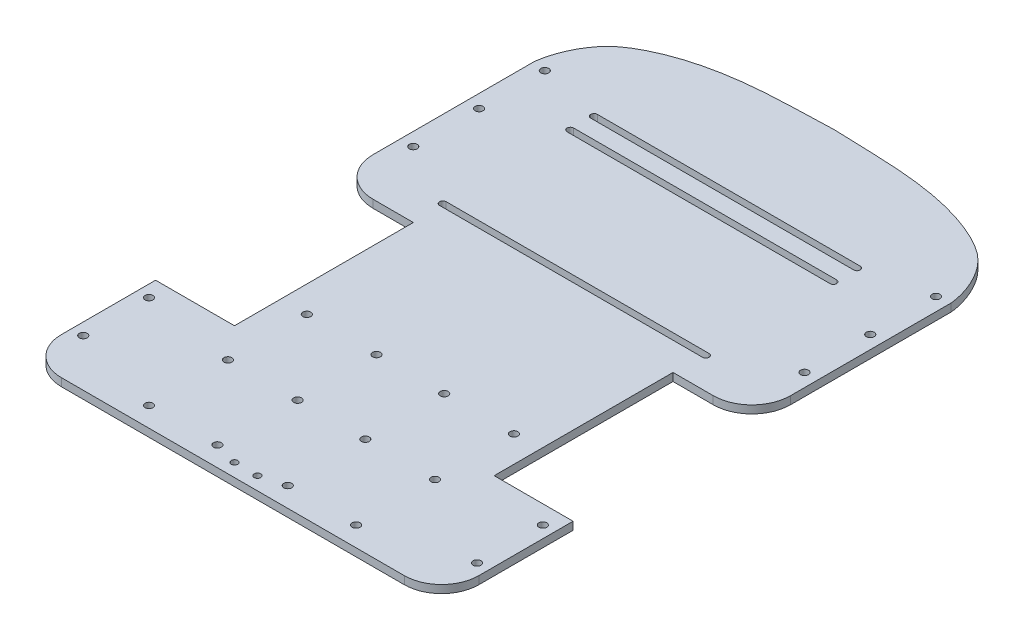
SolidWorks part; units mm, degrees
ref_plane "Front Plane" through (0, 0, 0) normal (0, 0, 1) x (1, 0, 0)
ref_plane "Top Plane" through (0, 0, 0) normal (0, 1, 0) x (1, 0, 0)
ref_plane "Right Plane" through (0, 0, 0) normal (1, 0, 0) x (0, 0, -1)
sketch "Sketch4" plane through (0, 0, 0) normal (0, 1, 0) x (1, 0, 0)
  line L0 (0, 128.6) -> (0, 0)
  line L1 (-65.209, 0) -> (0, 0)
  line L2 (-79.375, 14.166) -> (-79.375, 50)
  line L5 (622.9437, 519.1663) -> (1574.6175, 544.0867) construction
  line L6 (0, 228.6) -> (0, 188.6)
  line L7 (0, -55) -> (0, 55) construction
  line L9 (-79.375, 132.7) -> (-79.375, 193.786)
  line L10 (-49.375, 50) -> (-79.375, 50)
  line L12 (-49.375, 118) -> (-64.675, 118)
  line L14 (-50, 188.6) -> (0, 188.6)
  line L15 (-50, 186.1) -> (0, 186.1)
  line L16 (0, 186.1) -> (0, 179.6)
  line L17 (-50, 179.6) -> (0, 179.6)
  line L18 (-50, 177.1) -> (0, 177.1)
  line L19 (0, 177.1) -> (0, 131.1)
  line L20 (-50, 131.1) -> (0, 131.1)
  line L21 (-50, 128.6) -> (0, 128.6)
  line L22 (-49.375, 118) -> (-49.375, 50)
  arc A0 (-79.375, 14.166) -> (-65.209, 0) centre (-65.209, 14.166) ccw
  arc A1 (-79.375, 132.7) -> (-64.675, 118) centre (-64.675, 132.7) ccw
  circle A2 centre (-74.875, 43) radius 1.5
  circle A3 centre (-74.875, 18) radius 1.5
  circle A4 centre (-39.375, 7.5) radius 1.5
  circle A5 centre (-13.375, 7.5) radius 1.5
  circle A6 centre (-4.375, 5) radius 1.25
  circle A7 centre (-74.375, 143) radius 1.5
  circle A8 centre (-74.375, 168) radius 1.5
  circle A9 centre (-74.375, 193) radius 1.5
  arc A10 (-50, 188.6) -> (-50, 186.1) centre (-50, 187.35) ccw
  arc A11 (-50, 179.6) -> (-50, 177.1) centre (-50, 178.35) ccw
  arc A12 (-50, 131.1) -> (-50, 128.6) centre (-50, 129.85) ccw
  circle A13 centre (-39.375, 37.5) radius 1.5
  circle A14 centre (-39.375, 67.5) radius 1.5
  circle A15 centre (-12.875, 37.5) radius 1.5
  circle A16 centre (-12.875, 67.5) radius 1.5
  spline S0 degree 3 poles (-79.375, 193.786) (-78.784, 199.9641) (-73.9526, 211.6437) (-54.6605, 223.6018) (-29.5457, 228.1829) (-9.1881, 228.1715) (0, 228.6) knots 0 0 0 0 0.226113 0.32867 0.719907 1 1 1 1
  point P1 (-49.375, 50)
  dimension "D3" = 14.166
  dimension "D5" = 30
  dimension "D7" = 29.4
  dimension "D9" = 3
  dimension "D12" = 3
  dimension "D14" = 3
  dimension "D17" = 3
  dimension "D21" = 2.5
  dimension "D23" = 3
  dimension "D25" = 3
  dimension "D26" = 3
  dimension "D32" = 2.5
  dimension "D35" = 2.5
  dimension "D38" = 2.5
  dimension "D42" = 3
  dimension "D43" = 3
  dimension "D48" = 3
  dimension "D49" = 3
  dimension "D1" = 79.375
  dimension "D2" = 228.6
  dimension "D6" = 68
  dimension "D8" = 50
  dimension "D10" = 4.5
  dimension "D11" = 25
  dimension "4.5" = 4.5
  dimension "D13" = 40
  dimension "D15" = 7.5
  dimension "D16" = 7.5
  dimension "D18" = 26
  dimension "D19" = 5
  dimension "D20" = 9
  dimension "D22" = 25
  dimension "D24" = 5
  dimension "D27" = 25
  dimension "D28" = 25
  dimension "D29" = 5
  dimension "D30" = 5
  dimension "D31" = 50
  dimension "D33" = 40
  dimension "D34" = 2.5
  dimension "D36" = 9
  dimension "D37" = 50
  dimension "D39" = 48.5
  dimension "D40" = 50
  dimension "D41" = 30
  dimension "D44" = 30
  dimension "D45" = 26.5
  dimension "D46" = 30
  dimension "D47" = 30
  dimension "D50" = 30
extrude "Boss-Extrude2" add sketch "Sketch4" along normal blind 3
mirror "Mirror4" about plane through (0, 3, -177.1) normal (-1, 0, 0) of bodies 102
mirror "Mirror2"
